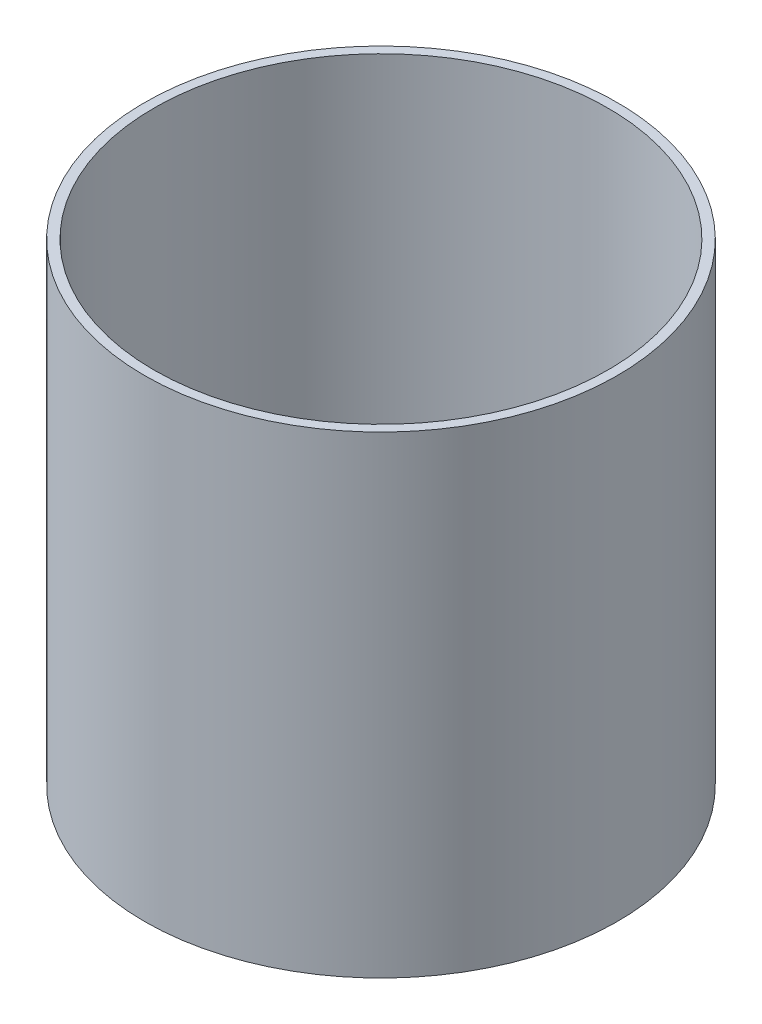
SolidWorks part; units mm, degrees
material "Acrylic (Medium-high impact)"
ref_plane "Front Plane" through (0, 0, 0) normal (0, 0, 1) x (1, 0, 0)
ref_plane "Top Plane" through (0, 0, 0) normal (0, 1, 0) x (1, 0, 0)
ref_plane "Right Plane" through (0, 0, 0) normal (1, 0, 0) x (0, 0, -1)
sketch "Sketch1" plane through (0, 0, 0) normal (0, 1, 0) x (1, 0, 0)
  circle A0 centre (0, 0) radius 250
  circle A1 centre (0, 0) radius 240
  dimension "D1" = 500
  dimension "D2" = 10
extrude "Boss-Extrude1" add sketch "Sketch1" along normal blind 500
